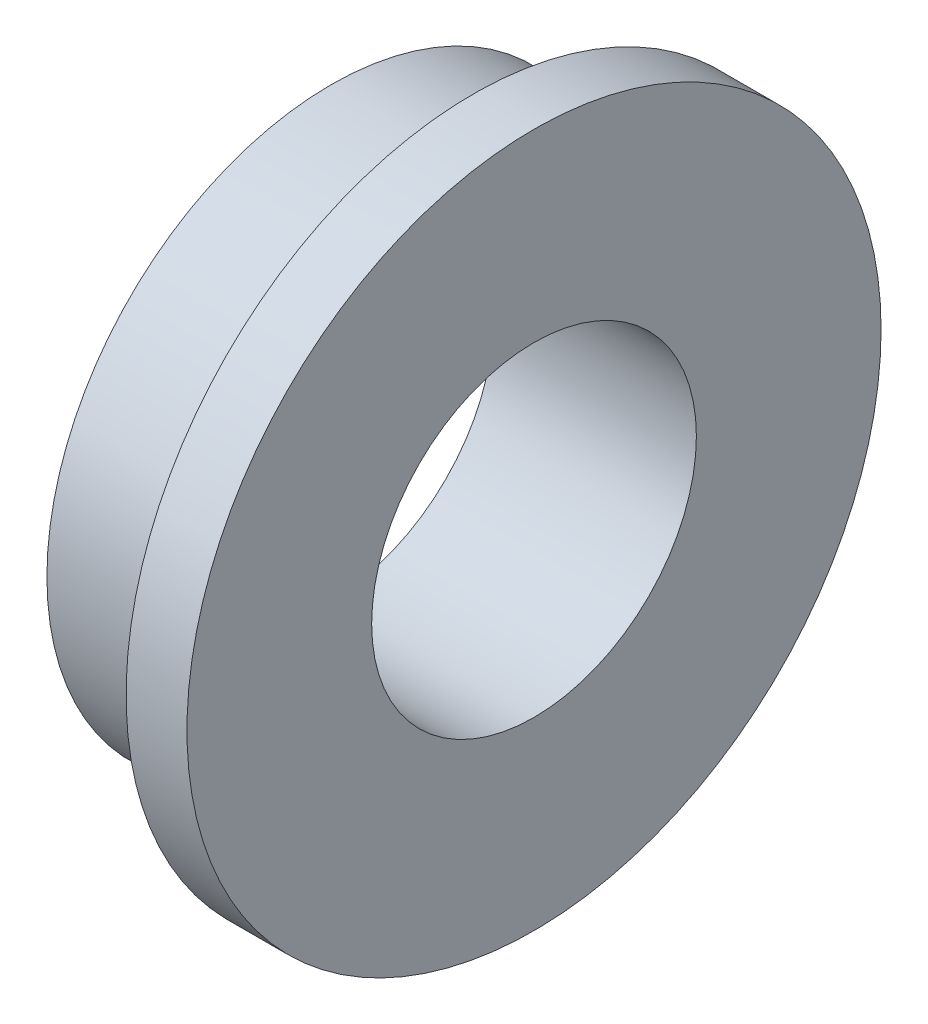
SolidWorks part; units mm, degrees
material "1.4000 (X6Cr13)"
ref_plane "Alzado" through (0, 0, 0) normal (1, 0, 0) x (0, 1, 0)
ref_plane "Planta" through (0, 0, 0) normal (0, 0, 1) x (0, 1, 0)
ref_plane "Vista lateral" through (0, 0, 0) normal (0, 1, 0) x (-1, 0, 0)
sketch "Croquis1" plane through (0, 0, 0) normal (0, 0, 1) x (0, 1, 0)
  line L0 (0, 0) -> (0, 5) construction
  line L1 (4, 0) -> (4, 5)
  line L2 (4, 5) -> (7, 5)
  line L3 (7, 5) -> (7, 1.5)
  line L4 (7, 1.5) -> (8.55, 1.5)
  line L5 (8.55, 1.5) -> (8.55, 0)
  line L6 (8.55, 0) -> (4, 0)
  point P5 (0, 0)
  dimension "D1" = 5
  dimension "D2" = 17.1
  dimension "D3" = 8
  dimension "D4" = 14
  dimension "D5" = 1.5
revolve "Revolución1" add sketch "Croquis1" angle 360 about L0
